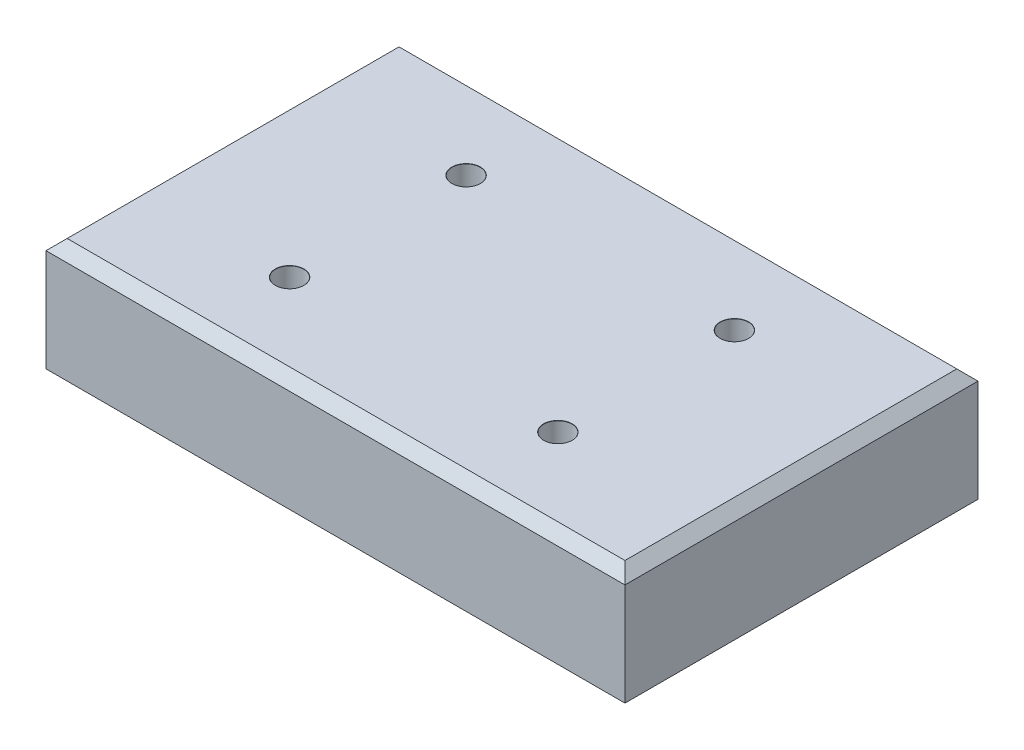
SolidWorks part; units mm, degrees
ref_plane "Front Plane" through (0, 0, 0) normal (0, 0, 1) x (1, 0, 0)
ref_plane "Top Plane" through (0, 0, 0) normal (0, 1, 0) x (1, 0, 0)
ref_plane "Right Plane" through (0, 0, 0) normal (1, 0, 0) x (0, 0, -1)
sketch "Sketch1" plane through (0, 0, 0) normal (0, 1, 0) x (1, 0, 0)
  line L0 (0, 40.4991) -> (0, -43.2182) construction
  line L1 (41, -25) -> (-41, -25)
  line L2 (41, -25) -> (41, 25)
  line L3 (41, 25) -> (-41, 25)
  line L4 (-41, -25) -> (-41, 25)
  line L5 (41, -25) -> (-41, 25) construction
  line L6 (41, 25) -> (-41, -25) construction
  line L7 (-55.4538, 0) -> (56.3124, 0) construction
  circle A0 centre (-19, 12.5) radius 2
  circle A1 centre (-19, -12.5) radius 2
  circle A2 centre (19, -12.5) radius 2
  circle A3 centre (19, 12.5) radius 2
  point P0 (0, 0)
  dimension "D6" = 4
  dimension "D7" = 4
  dimension "D1" = 82
  dimension "D2" = 50
  dimension "D3" = 25
  dimension "D4" = 12.5
  dimension "D5" = 12.5
  dimension "D8" = 38
extrude "Boss-Extrude1" add sketch "Sketch1" along normal blind 16 contours L4 L1 L2 L3 A2 A1 A0 A3 | A0 | A2 | A3 | A1
sketch "Sketch2" plane through (0, 16, 0) normal (0, 1, 0) x (1, 0, 0)
  line L4 (-41, -25) -> (41, -25)
  line L5 (-41, 25) -> (-41, -25)
  line L6 (41, 25) -> (-41, 25)
  line L7 (41, -25) -> (41, 25)
  line L8 (-41, -25) -> (41, -25)
  line L9 (-41, 25) -> (-41, -25)
  line L10 (41, 25) -> (-41, 25)
  line L11 (41, -25) -> (41, 25)
  circle A1 centre (-19, -12.5) radius 2
  circle A2 centre (-19, -12.5) radius 2
  circle A3 centre (-19, 12.5) radius 2
  circle A4 centre (-19, 12.5) radius 2
  circle A5 centre (19, 12.5) radius 2
  circle A6 centre (19, 12.5) radius 2
  circle A7 centre (19, -12.5) radius 2
  circle A8 centre (19, -12.5) radius 2
  dimension "D1" = 0
  dimension "D2" = 0
  dimension "D3" = 0
  dimension "D4" = 0
  dimension "D5" = 0
extrude "Cut-Extrude1" cut sketch "Sketch2" against normal blind 6 contours A2 | A4 | A8 | A6
hole_wizard "M4x0.7 Tapped Hole1" positions "3DSketch1" profile "Sketch3" tap size "M4x0.7" standard "ANSI Metric"
sketch3d "3DSketch1"
  line L0 (-19, 10, -12.5) -> (-19, 16, -12.5) construction
  line L1 (19, 10, -12.5) -> (19, 16, -12.5) construction
  line L2 (19, 10, 12.5) -> (19, 16, 12.5) construction
  line L3 (-19, 10, 12.5) -> (-19, 16, 12.5) construction
  point P0 (-19, 16, -12.5)
  point P4 (19, 16, -12.5)
  point P8 (19, 16, 12.5)
  point P12 (-19, 16, 12.5)
sketch "Sketch3" plane through (-19, 16, -12.5) normal (1, 0, 0) x (0, 0, 1)
  line L0 (0, 0) -> (0, 8)
  line L1 (0, 8) -> (1.65, 7.0086)
  line L2 (1.65, 7.0086) -> (1.65, 0.375)
  line L3 (1.65, 0.375) -> (2.025, 0)
  line L5 (2.025, 0) -> (0, 0)
  line L6 (-1.65, 0.375) -> (-2.025, 0) construction
  line L10 (0, 8) -> (-1.65, 7.0086) construction
  line L11 (0, -6.35) -> (0, 107.95) construction
  dimension "Tap Drill Dia." = 3.3
  dimension "Tap Drill Depth" = 8
  dimension "Near C'Sink Dia." = 4.05
  dimension "Near C'Sink Angle" = 90
  dimension "Drill Angle" = 118
cosmetic thread "Hole Thread1" parameters "D1"=8, "D2"=4
cosmetic thread "Hole Thread2" parameters "D1"=8, "D2"=4
cosmetic thread "Hole Thread3" parameters "D1"=8, "D2"=4
cosmetic thread "Hole Thread4" parameters "D1"=8, "D2"=4
chamfer "Chamfer1" distance 1.5 angle 45 4 edges at (0, 16, -25) (-41, 16, 0) (0, 16, 25) (41, 16, 0)
